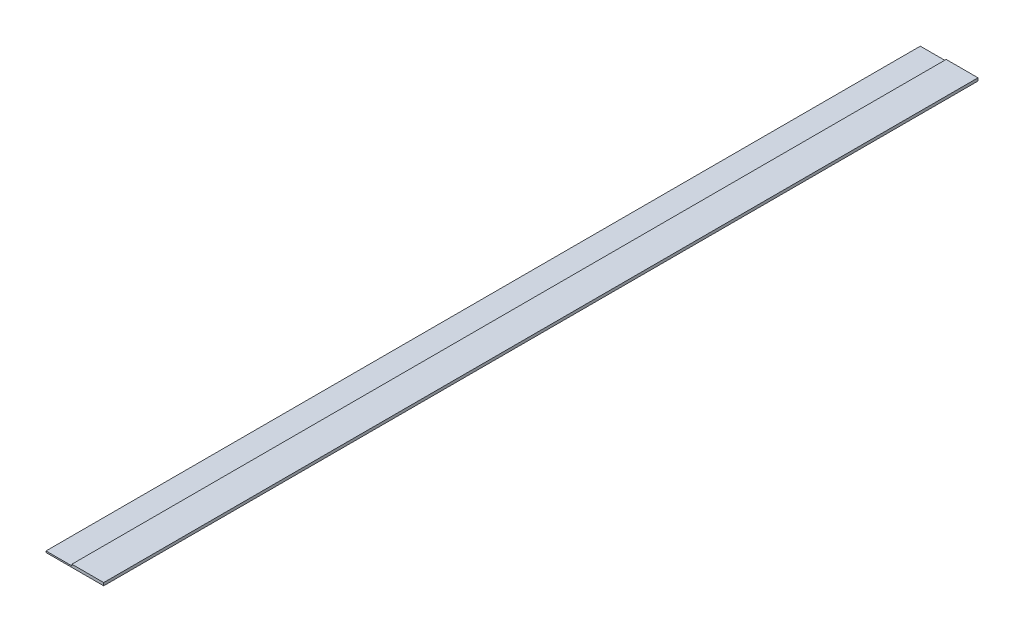
SolidWorks part; units mm, degrees
material "ASTM A500 Grade B Steel"
ref_plane "Front Plane" through (0, 0, 0) normal (0, 0, 1) x (1, 0, 0)
ref_plane "Top Plane" through (0, 0, 0) normal (0, 1, 0) x (1, 0, 0)
ref_plane "Right Plane" through (0, 0, 0) normal (1, 0, 0) x (0, 0, -1)
sketch "Sketch1" plane through (0, 0, 5872.3042) normal (0, 0, 1) x (1, 0, 0)
  line L0 (853.1287, 2006.3936) -> (1042.8583, 2006.3936)
  line L1 (1042.8583, 2006.3936) -> (1042.8583, 2015.0895)
  line L2 (779.9767, 2017.9506) -> (771.8487, 2017.9506)
  line L4 (2801.0139, 2015.0895) -> (2800.7034, 2022.2015)
  line L5 (2800.7034, 2022.2015) -> (853.1287, 2022.2015)
  line L6 (853.1287, 2022.2015) -> (853.1287, 2015.0895)
  line L7 (853.1287, 2015.0895) -> (2801.0139, 2015.0895)
  line L8 (2801.0139, 2015.0895) -> (2800.7034, 2022.2015)
  line L9 (2800.7034, 2022.2015) -> (853.1287, 2022.2015)
  line L10 (853.1287, 2022.2015) -> (853.1287, 2015.0895)
  line L11 (853.1287, 2015.0895) -> (2801.0139, 2015.0895)
  line L12 (698.6967, 2168.4456) -> (698.6967, 2156.8886)
  line L13 (698.6967, 2156.8886) -> (771.8487, 2156.8886)
  line L14 (771.8487, 2156.8886) -> (771.8487, 2017.9506)
  line L15 (771.8487, 2017.9506) -> (698.6967, 2017.9506)
  line L16 (698.6967, 2017.9506) -> (698.6967, 2006.3936)
  line L17 (698.6967, 2006.3936) -> (853.1287, 2006.3936)
  line L18 (853.1287, 2006.3936) -> (853.1287, 2017.9506)
  line L19 (853.1287, 2017.9506) -> (779.9767, 2017.9506)
  line L20 (779.9767, 2017.9506) -> (779.9767, 2156.8886)
  line L21 (779.9767, 2156.8886) -> (853.1287, 2156.8886)
  line L22 (853.1287, 2156.8886) -> (853.1287, 2168.4456)
  line L23 (853.1287, 2168.4456) -> (698.6967, 2168.4456)
  line L24 (698.6967, 2168.4456) -> (698.6967, 2156.8886)
  line L25 (698.6967, 2156.8886) -> (771.8487, 2156.8886)
  line L26 (771.8487, 2156.8886) -> (771.8487, 2017.9506)
  line L27 (771.8487, 2017.9506) -> (698.6967, 2017.9506)
  line L28 (698.6967, 2017.9506) -> (698.6967, 2006.3936)
  line L29 (698.6967, 2006.3936) -> (853.1287, 2006.3936)
  line L30 (853.1287, 2006.3936) -> (853.1287, 2017.9506)
  line L31 (853.1287, 2017.9506) -> (779.9767, 2017.9506)
  line L32 (779.9767, 2017.9506) -> (779.9767, 2156.8886)
  line L33 (779.9767, 2156.8886) -> (853.1287, 2156.8886)
  line L34 (853.1287, 2156.8886) -> (853.1287, 2168.4456)
  line L35 (853.1287, 2168.4456) -> (698.6967, 2168.4456)
  line L36 (1042.8583, 2006.3936) -> (698.6967, 2006.3936)
  line L37 (1042.8583, 2006.3936) -> (1042.8583, 1998.078)
  line L38 (1042.8583, 1998.078) -> (698.6967, 1998.078)
  line L39 (698.6967, 2006.3936) -> (698.6967, 1998.078)
  line M22 (698.6967, 2006.3936) -> (853.1287, 2006.3936)
  line M23 (853.1287, 2006.3936) -> (853.1287, 2017.9506)
  dimension "D1" = 0
  dimension "D2" = 0
extrude "Boss-Extrude1" add sketch "Sketch1" against normal up to surface (5214.4 mm away) contours L39 L38 L37 L0 M22 | L11 L0 L1 M23
sketch "Sketch2" plane through (0, 1998.078, 0) normal (0, -1, 0) x (1, 0, 0)
  line L2 (698.6967, 657.9042) -> (698.6967, 5872.3042) construction
  line L3 (698.6967, 3265.1042) -> (1042.8583, 3265.1042) construction
  line L4 (1042.8583, 657.9042) -> (1042.8583, 5872.3042) construction
  line L5 (718.3775, 3417.5042) -> (1023.1775, 3417.5042)
  line L6 (718.3775, 3417.5042) -> (718.3775, 3112.7042)
  line L7 (718.3775, 3112.7042) -> (1023.1775, 3112.7042)
  line L8 (1023.1775, 3417.5042) -> (1023.1775, 3112.7042)
  line L9 (718.3775, 3417.5042) -> (1023.1775, 3112.7042) construction
  line L10 (718.3775, 3112.7042) -> (1023.1775, 3417.5042) construction
  point P0 (870.7775, 3265.1042)
  point P2 (870.7775, 3265.1042)
  dimension "D1" = 304.8
  dimension "D2" = 304.8
split line "Split Line1" [suppressed]
sketch "Sketch3" plane through (0, 1998.078, 0) normal (0, -1, 0) x (-1, 0, 0)
  line L0 (-870.7775, -3265.1042) -> (-870.7775, -657.9042) construction
  line L2 (-698.6967, -657.9042) -> (-698.6967, -5872.3042) construction
  line L3 (-698.6967, -3265.1042) -> (-1042.8583, -3265.1042) construction
  line L4 (-1042.8583, -657.9042) -> (-1042.8583, -5872.3042) construction
  line L5 (-1042.8583, -657.9042) -> (-698.6967, -657.9042) construction
  line L6 (-870.7775, -5872.3042) -> (-870.7775, -3265.1042) construction
  line L7 (-1042.8583, -5872.3042) -> (-698.6967, -5872.3042) construction
  line L9 (-718.3775, -4721.1042) -> (-1023.1775, -4721.1042)
  line L10 (-718.3775, -4721.1042) -> (-718.3775, -4416.3042)
  line L11 (-718.3775, -4416.3042) -> (-1023.1775, -4416.3042)
  line L12 (-1023.1775, -4721.1042) -> (-1023.1775, -4416.3042)
  line L13 (-718.3775, -4721.1042) -> (-1023.1775, -4416.3042) construction
  line L14 (-718.3775, -4416.3042) -> (-1023.1775, -4721.1042) construction
  line L15 (-718.3775, -2113.9042) -> (-1023.1775, -2113.9042)
  line L16 (-718.3775, -2113.9042) -> (-718.3775, -1809.1042)
  line L17 (-718.3775, -1809.1042) -> (-1023.1775, -1809.1042)
  line L18 (-1023.1775, -2113.9042) -> (-1023.1775, -1809.1042)
  line L19 (-718.3775, -2113.9042) -> (-1023.1775, -1809.1042) construction
  line L20 (-718.3775, -1809.1042) -> (-1023.1775, -2113.9042) construction
  point P11 (-870.7775, -4568.7042)
  point P18 (-870.7775, -1961.5042)
  dimension "D1" = 304.8
  dimension "D2" = 304.8
  dimension "D3" = 304.8
  dimension "D4" = 304.8
split line "Split Line2"
